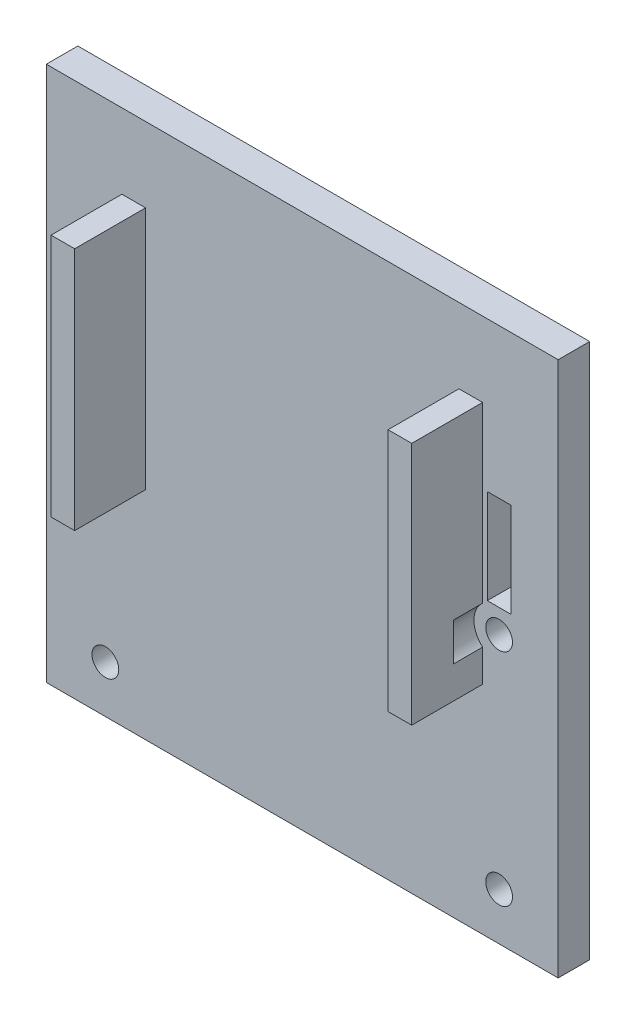
SolidWorks part; units mm, degrees
ref_plane "前视基准面" through (0, 0, 0) normal (0, 0, 1) x (1, 0, 0)
ref_plane "上视基准面" through (0, 0, 0) normal (0, 1, 0) x (1, 0, 0)
ref_plane "右视基准面" through (0, 0, 0) normal (1, 0, 0) x (0, 0, -1)
other "Configuration Table"
sketch "Sketch_Radar_seat" plane through (0, 0, 0) normal (0, 0, 1) x (1, 0, 0)
  line L0 (32.5, -43) -> (32.5, 25)
  line L1 (32.5, 25) -> (-32.5, 25)
  line L2 (-32.5, 25) -> (-32.5, -43)
  line L3 (-32.5, -43) -> (32.5, -43)
extrude "Radar_seat" add sketch "Sketch_Radar_seat" along normal blind 4 from offset 0
sketch "Sketch_Lateral_stops" plane through (0, 0, 0) normal (0, 0, 1) x (1, 0, 0)
  line L0 (-22.9, -15.5) -> (-22.9, 15.5)
  line L1 (-22.9, 15.5) -> (-19.9, 15.5)
  line L2 (-19.9, 15.5) -> (-19.9, -15.5)
  line L3 (-19.9, -15.5) -> (-22.9, -15.5)
  line L4 (19.9, -15.5) -> (19.9, 15.5)
  line L5 (19.9, 15.5) -> (22.9, 15.5)
  line L6 (22.9, 15.5) -> (22.9, -15.5)
  line L7 (22.9, -15.5) -> (19.9, -15.5)
extrude "Lateral_stops" add sketch "Sketch_Lateral_stops" along normal blind 9 from offset 4
sketch "Sketch_Post_M3" plane through (0, 0, 0) normal (0, 0, 1) x (1, 0, 0)
  circle A0 centre (-25, -37) radius 1.7
  circle A1 centre (-25, -9) radius 1.7
  circle A2 centre (25, -37) radius 1.7
  circle A3 centre (25, -9) radius 1.7
  dimension "D1" = 3.4
  dimension "D4" = 3.4
  dimension "D7" = 3.4
  dimension "D10" = 3.4
  dimension "D2" = 25
  dimension "D3" = 37
  dimension "D5" = 25
  dimension "D6" = 9
  dimension "D8" = 25
  dimension "D9" = 37
  dimension "D11" = 25
  dimension "D12" = 9
extrude "Post_M3" cut sketch "Sketch_Post_M3" along normal blind 7 from offset 1
sketch "Sketch_Top_screw_head_reliefs" plane through (0, 0, 0) normal (0, 0, 1) x (1, 0, 0)
  circle A0 centre (-25, -9) radius 3.2
  circle A1 centre (25, -9) radius 3.2
  dimension "D1" = 6.4
  dimension "D4" = 6.4
  dimension "D2" = 25
  dimension "D3" = 9
  dimension "D5" = 25
  dimension "D6" = 9
extrude "Top_screw_head_reliefs" cut sketch "Sketch_Top_screw_head_reliefs" along normal blind 3.7 from offset 4
sketch "Sketch_Retention_strap_slots" plane through (0, 0, 0) normal (0, 0, 1) x (1, 0, 0)
  line L0 (-26.5, -6) -> (-26.5, 6)
  line L1 (-26.5, 6) -> (-23.5, 6)
  line L2 (-23.5, 6) -> (-23.5, -6)
  line L3 (-23.5, -6) -> (-26.5, -6)
  line L4 (23.5, -6) -> (23.5, 6)
  line L5 (23.5, 6) -> (26.5, 6)
  line L6 (26.5, 6) -> (26.5, -6)
  line L7 (26.5, -6) -> (23.5, -6)
extrude "Retention_strap_slots" cut sketch "Sketch_Retention_strap_slots" along normal blind 7 from offset 1
